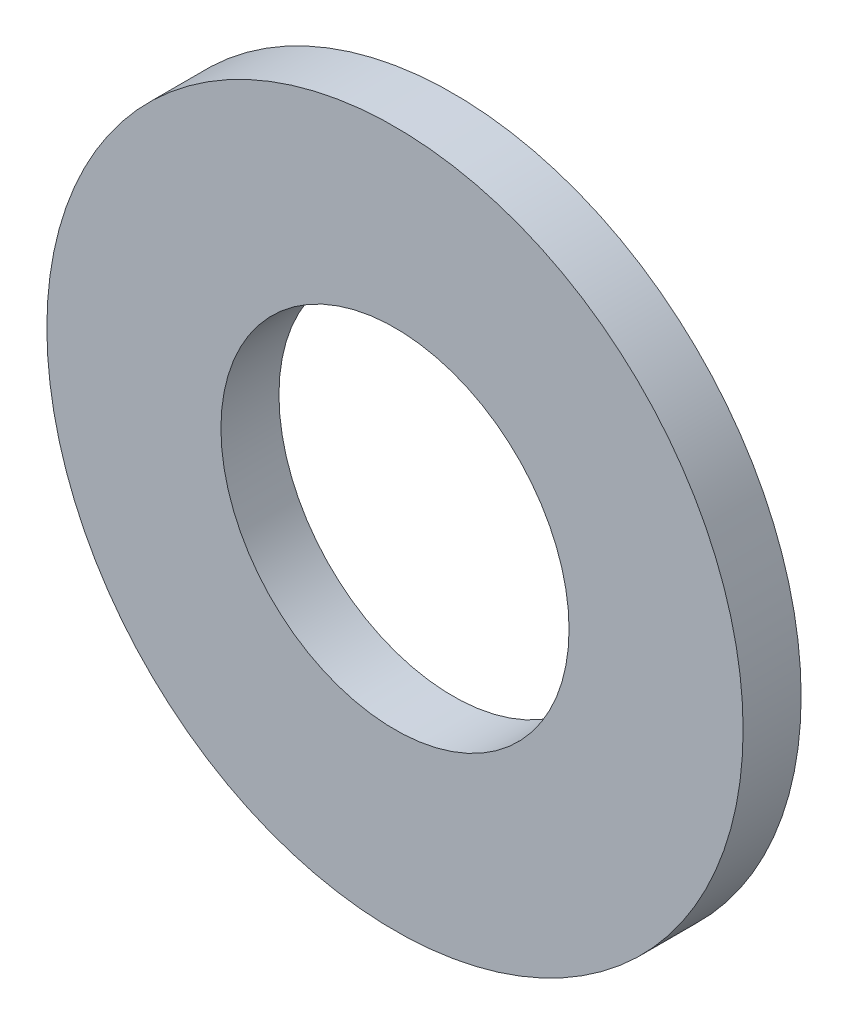
SolidWorks part; units mm, degrees
ref_plane "Front Plane" through (0, 0, 0) normal (0, 0, 1) x (1, 0, 0)
ref_plane "Top Plane" through (0, 0, 0) normal (0, 1, 0) x (1, 0, 0)
ref_plane "Right Plane" through (0, 0, 0) normal (1, 0, 0) x (0, 0, -1)
sketch "Sketch1" plane through (0, 0, 0) normal (0, 0, 1) x (1, 0, 0)
  circle A0 centre (0, 0) radius 12
  circle A1 centre (0, 0) radius 24
  dimension "D1" = 48
  dimension "D2" = 24
extrude "Boss-Extrude1" add sketch "Sketch1" along normal blind 4
